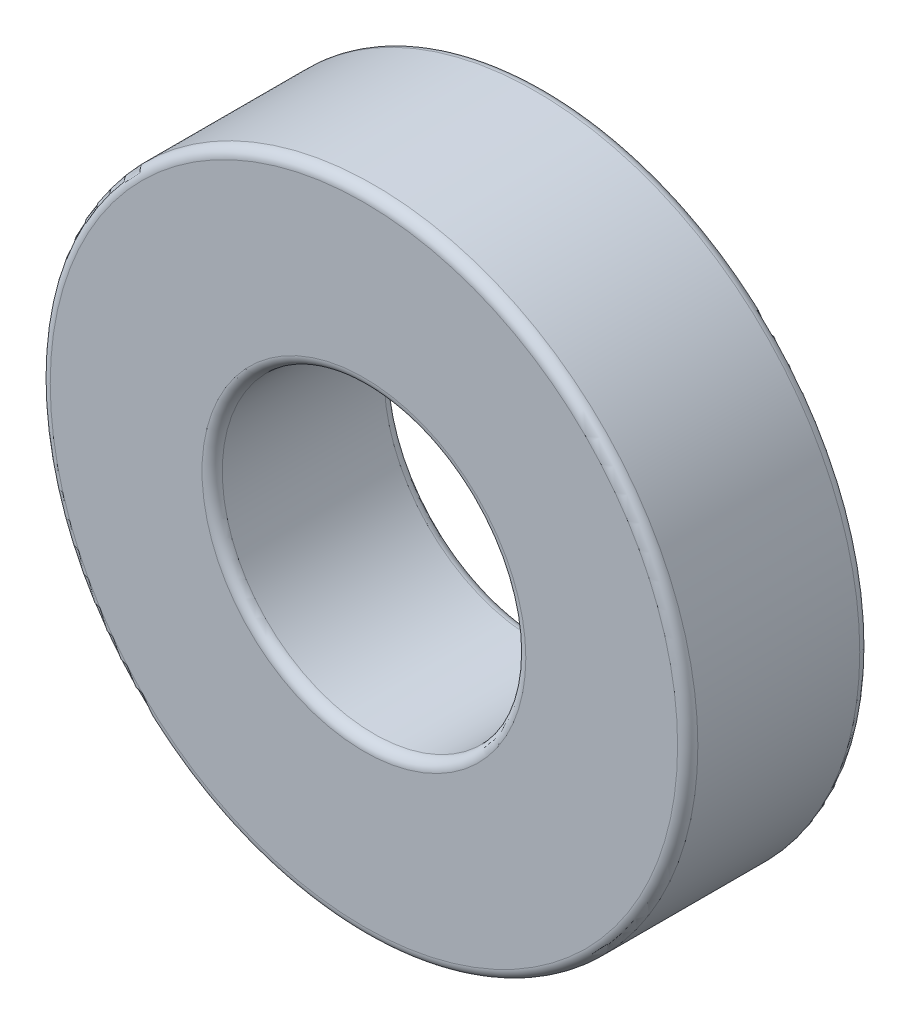
SolidWorks part; units mm, degrees
ref_plane "Front" through (0, 0, 0) normal (0, 0, 1) x (1, 0, 0)
ref_plane "Top" through (0, 0, 0) normal (0, 1, 0) x (1, 0, 0)
ref_plane "Right" through (0, 0, 0) normal (1, 0, 0) x (0, 0, -1)
sketch "Esquisse1" plane through (0, 0, 0) normal (0, 0, 1) x (1, 0, 0)
  circle A0 centre (0, 0) radius 7.5
  circle A1 centre (0, 0) radius 16
  dimension "D1" = 15
  dimension "D2" = 32
extrude "Boss.-Extru.1" add sketch "Esquisse1" along normal blind 9
fillet "Congé1" radius 0.5 4 edges at (7.5, 0, 0) (16, 0, 0) (7.5, 0, 9) (16, 0, 9)
